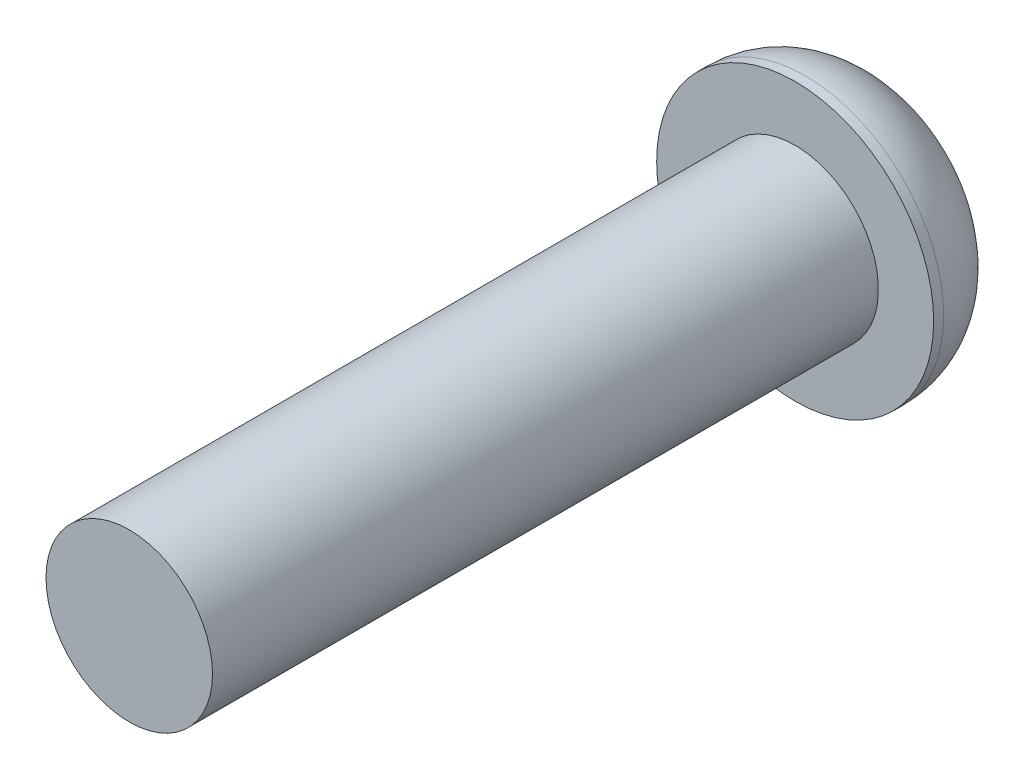
SolidWorks part; units mm, degrees
ref_plane "Front Plane" through (0, 0, 0) normal (0, 0, 1) x (1, 0, 0)
ref_plane "Top Plane" through (0, 0, 0) normal (0, 1, 0) x (1, 0, 0)
ref_plane "Right Plane" through (0, 0, 0) normal (1, 0, 0) x (0, 0, -1)
sketch "Sketch1" plane through (0, 0, 0) normal (0, 0, 1) x (1, 0, 0)
  circle A0 centre (0, 0) radius 2.5
  dimension "D1" = 5
extrude "Boss-Extrude1" add sketch "Sketch1" along normal blind 20
sketch "Sketch2" plane through (0, 0, 0) normal (0, 0, -1) x (-1, 0, 0)
  circle A0 centre (0, 0) radius 4.1596
extrude "Boss-Extrude2" add sketch "Sketch2" along normal blind 2.8
fillet "Fillet1" radius 2.5 1 edges at (-4.1596, 0, -2.8)
sketch "Sketch3" plane through (0, 0, -2.8) normal (0, 0, -1) x (-1, 0, 0)
  line L1 (1.3924, -0.6365) -> (1.2475, 0.8876)
  line L2 (1.2475, 0.8876) -> (-0.145, 1.5241)
  line L3 (-0.145, 1.5241) -> (-1.3924, 0.6365)
  line L4 (-1.3924, 0.6365) -> (-1.2475, -0.8876)
  line L5 (-1.2475, -0.8876) -> (0.145, -1.5241)
  line L6 (0.145, -1.5241) -> (1.3924, -0.6365)
  circle A0 centre (0, 0) radius 1.3259 construction
extrude "Cut-Extrude1" cut sketch "Sketch3" against normal blind 2
